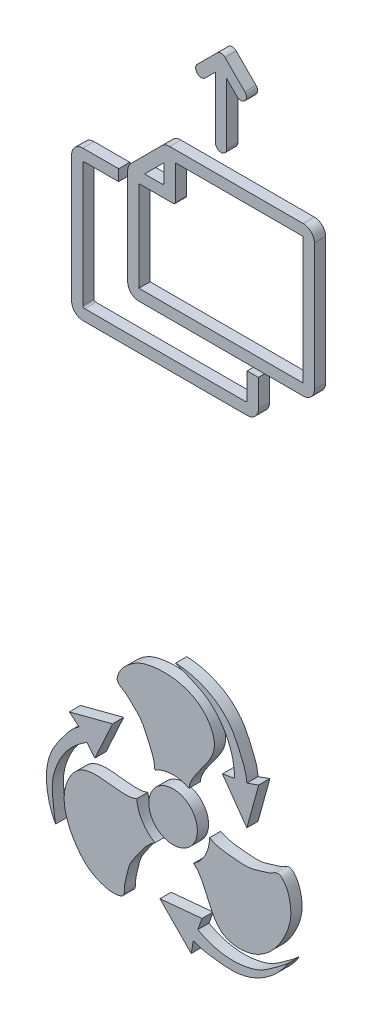
SolidWorks part; units mm, degrees
ref_plane "Plan de face" through (0, 0, 0) normal (0, 0, 1) x (1, 0, 0)
ref_plane "Plan de dessus" through (0, 0, 0) normal (0, 1, 0) x (1, 0, 0)
ref_plane "Plan de droite" through (0, 0, 0) normal (1, 0, 0) x (0, 0, -1)
sketch "Esquisse1" plane through (0, 0, 0) normal (0, 0, 1) x (1, 0, 0)
  line L0 (79.9524, -9.5695) -> (79.2967, -9.6893) construction
  line L1 (79.2967, -9.6893) -> (80.6081, -11.5354) construction
  line L2 (80.6081, -11.5354) -> (81.2446, -9.231) construction
  line L3 (81.2446, -9.231) -> (80.6081, -9.4601) construction
  line L4 (72.0398, -11.8622) -> (72.4714, -12.3701)
  line L5 (72.4714, -12.3701) -> (73.4145, -10.3114)
  line L6 (73.4145, -10.3114) -> (71.1005, -10.9123)
  line L7 (71.1005, -10.9123) -> (71.6172, -11.349)
  line L8 (72.0398, -11.8622) -> (72.4714, -12.3701)
  line L9 (72.4714, -12.3701) -> (73.4145, -10.3114)
  line L10 (73.4145, -10.3114) -> (71.1005, -10.9123)
  line L11 (71.1005, -10.9123) -> (71.6172, -11.349)
  line L12 (77.9816, -17.5683) -> (78.2057, -16.9406) construction
  line L13 (78.2057, -16.9406) -> (75.9512, -17.1532) construction
  line L14 (75.9512, -17.1532) -> (77.6286, -18.8567) construction
  line L15 (77.6286, -18.8567) -> (77.7484, -18.1908) construction
  line L16 (79.9524, -9.5695) -> (79.2967, -9.6893)
  line L17 (79.2967, -9.6893) -> (80.6081, -11.5354)
  line L18 (80.6081, -11.5354) -> (81.2446, -9.231)
  line L19 (81.2446, -9.231) -> (80.6081, -9.4601)
  line L20 (77.9816, -17.5683) -> (78.2057, -16.9406)
  line L21 (78.2057, -16.9406) -> (75.9512, -17.1532)
  line L22 (75.9512, -17.1532) -> (77.6286, -18.8567)
  line L23 (77.6286, -18.8567) -> (77.7484, -18.1908)
  line L24 (78.3769, 22.1272) -> (78.9254, 22.6757) construction
  line L25 (78.9254, 22.6757) -> (78.9254, 19.4) construction
  line L26 (79.5254, 19.4) -> (79.5254, 22.6757) construction
  line L27 (79.5254, 22.6757) -> (80.0739, 22.1272) construction
  line L28 (80.4982, 22.5515) -> (79.4375, 23.6121) construction
  line L29 (79.0133, 23.6121) -> (77.9526, 22.5515) construction
  line L30 (74.8254, 10) -> (83.6254, 10) construction
  line L31 (84.2254, 10.6) -> (84.2254, 17.4) construction
  line L32 (83.6254, 18) -> (76.4739, 18) construction
  line L33 (76.0497, 17.8243) -> (74.4011, 16.1757) construction
  line L34 (74.2254, 15.7515) -> (74.2254, 10.6) construction
  line L35 (71.8254, 7.6) -> (80.6254, 7.6) construction
  line L36 (81.2254, 8.2) -> (81.2254, 9.6641) construction
  line L37 (81.2254, 9.6641) -> (80.6254, 9.6641) construction
  line L38 (80.6254, 9.6641) -> (80.6254, 8.3) construction
  line L39 (80.5254, 8.2) -> (71.9254, 8.2) construction
  line L40 (71.8254, 8.3) -> (71.8254, 14.9) construction
  line L41 (71.9254, 15) -> (73.7394, 15) construction
  line L42 (73.7394, 15) -> (73.7394, 15.6) construction
  line L43 (73.7394, 15.6) -> (71.8254, 15.6) construction
  line L44 (71.2254, 15) -> (71.2254, 8.2) construction
  line L45 (78.3769, 22.1272) -> (78.9254, 22.6757)
  line L46 (78.9254, 22.6757) -> (78.9254, 19.4)
  line L47 (79.5254, 19.4) -> (79.5254, 22.6757)
  line L48 (79.5254, 22.6757) -> (80.0739, 22.1272)
  line L49 (80.4982, 22.5515) -> (79.4375, 23.6121)
  line L50 (79.0133, 23.6121) -> (77.9526, 22.5515)
  line L51 (74.8254, 10) -> (83.6254, 10)
  line L52 (84.2254, 10.6) -> (84.2254, 17.4)
  line L53 (83.6254, 18) -> (76.4739, 18)
  line L54 (76.0497, 17.8243) -> (74.4011, 16.1757)
  line L55 (74.2254, 15.7515) -> (74.2254, 10.6)
  line L56 (71.8254, 7.6) -> (80.6254, 7.6)
  line L57 (81.2254, 8.2) -> (81.2254, 9.6641)
  line L58 (81.2254, 9.6641) -> (80.6254, 9.6641)
  line L59 (80.6254, 9.6641) -> (80.6254, 8.3)
  line L60 (80.5254, 8.2) -> (71.9254, 8.2)
  line L61 (71.8254, 8.3) -> (71.8254, 14.9)
  line L62 (71.9254, 15) -> (73.7394, 15)
  line L63 (73.7394, 15) -> (73.7394, 15.6)
  line L64 (73.7394, 15.6) -> (71.8254, 15.6)
  line L65 (71.2254, 15) -> (71.2254, 8.2)
  line L69 (75.1254, 16.0515) -> (76.0739, 16.0515)
  line L70 (76.1739, 16.1515) -> (76.1739, 17.1)
  line L71 (76.1739, 17.1) -> (75.1254, 16.0515)
  line L72 (76.6739, 15.4515) -> (74.8254, 15.4515)
  line L73 (74.8254, 15.4515) -> (74.8254, 10.6)
  line L74 (74.8254, 10.6) -> (83.6254, 10.6)
  line L75 (83.6254, 10.6) -> (83.6254, 17.4)
  line L76 (83.6254, 17.4) -> (76.7739, 17.4)
  line L77 (76.7739, 17.4) -> (76.7739, 15.5515)
  line L78 (76.6739, 15.4515) -> (74.8254, 15.4515)
  line L79 (74.8254, 15.4515) -> (74.8254, 10.6)
  line L80 (74.8254, 10.6) -> (83.6254, 10.6)
  line L81 (83.6254, 10.6) -> (83.6254, 17.4)
  line L82 (83.6254, 17.4) -> (76.7739, 17.4)
  line L83 (76.7739, 17.4) -> (76.7739, 15.5515)
  line L84 (75.1254, 16.0515) -> (76.0739, 16.0515)
  line L85 (76.1739, 16.1515) -> (76.1739, 17.1)
  line L86 (76.1739, 17.1) -> (75.1254, 16.0515)
  arc A0 (77.7481, -14.6167) -> (78.6079, -12.9946) centre (76.6579, -13) ccw construction
  arc A1 (74.7127, -13.1358) -> (75.6876, -14.6914) centre (76.6579, -13) ccw
  arc A2 (74.7127, -13.1358) -> (75.6876, -14.6914) centre (76.6579, -13) ccw
  circle A3 centre (76.6579, -13) radius 1.3 construction
  arc A4 (77.513, -11.2475) -> (75.6783, -11.314) centre (76.6579, -13) ccw construction
  arc A5 (77.7481, -14.6167) -> (78.6079, -12.9946) centre (76.6579, -13) ccw
  circle A6 centre (76.6579, -13) radius 1.3
  arc A7 (77.513, -11.2475) -> (75.6783, -11.314) centre (76.6579, -13) ccw
  arc A8 (78.9254, 19.4) -> (79.5254, 19.4) centre (79.2254, 19.4) ccw construction
  arc A9 (80.0739, 22.1272) -> (80.4982, 22.5515) centre (80.2861, 22.3393) ccw construction
  arc A10 (79.4375, 23.6121) -> (79.0133, 23.6121) centre (79.2254, 23.4) ccw construction
  arc A11 (77.9526, 22.5515) -> (78.3769, 22.1272) centre (78.1647, 22.3393) ccw construction
  arc A12 (74.2254, 10.6) -> (74.8254, 10) centre (74.8254, 10.6) ccw construction
  arc A13 (83.6254, 10) -> (84.2254, 10.6) centre (83.6254, 10.6) ccw construction
  arc A14 (84.2254, 17.4) -> (83.6254, 18) centre (83.6254, 17.4) ccw construction
  arc A15 (76.4739, 18) -> (76.0497, 17.8243) centre (76.4739, 17.4) ccw construction
  arc A16 (74.4011, 16.1757) -> (74.2254, 15.7515) centre (74.8254, 15.7515) ccw construction
  arc A17 (71.2254, 8.2) -> (71.8254, 7.6) centre (71.8254, 8.2) ccw construction
  arc A18 (80.6254, 7.6) -> (81.2254, 8.2) centre (80.6254, 8.2) ccw construction
  arc A19 (80.5254, 8.2) -> (80.6254, 8.3) centre (80.5254, 8.3) ccw construction
  arc A20 (71.8254, 8.3) -> (71.9254, 8.2) centre (71.9254, 8.3) ccw construction
  arc A21 (71.9254, 15) -> (71.8254, 14.9) centre (71.9254, 14.9) ccw construction
  arc A22 (71.8254, 15.6) -> (71.2254, 15) centre (71.8254, 15) ccw construction
  arc A23 (78.9254, 19.4) -> (79.5254, 19.4) centre (79.2254, 19.4) ccw
  arc A24 (80.0739, 22.1272) -> (80.4982, 22.5515) centre (80.2861, 22.3393) ccw
  arc A25 (79.4375, 23.6121) -> (79.0133, 23.6121) centre (79.2254, 23.4) ccw
  arc A26 (77.9526, 22.5515) -> (78.3769, 22.1272) centre (78.1647, 22.3393) ccw
  arc A27 (74.2254, 10.6) -> (74.8254, 10) centre (74.8254, 10.6) ccw
  arc A28 (83.6254, 10) -> (84.2254, 10.6) centre (83.6254, 10.6) ccw
  arc A29 (84.2254, 17.4) -> (83.6254, 18) centre (83.6254, 17.4) ccw
  arc A30 (76.4739, 18) -> (76.0497, 17.8243) centre (76.4739, 17.4) ccw
  arc A31 (74.4011, 16.1757) -> (74.2254, 15.7515) centre (74.8254, 15.7515) ccw
  arc A32 (71.2254, 8.2) -> (71.8254, 7.6) centre (71.8254, 8.2) ccw
  arc A33 (80.6254, 7.6) -> (81.2254, 8.2) centre (80.6254, 8.2) ccw
  arc A34 (80.5254, 8.2) -> (80.6254, 8.3) centre (80.5254, 8.3) ccw
  arc A35 (71.8254, 8.3) -> (71.9254, 8.2) centre (71.9254, 8.3) ccw
  arc A36 (71.9254, 15) -> (71.8254, 14.9) centre (71.9254, 14.9) ccw
  arc A37 (71.8254, 15.6) -> (71.2254, 15) centre (71.8254, 15) ccw
  arc A39 (76.6739, 15.4515) -> (76.7739, 15.5515) centre (76.6739, 15.5515) ccw
  arc A40 (76.6739, 15.4515) -> (76.7739, 15.5515) centre (76.6739, 15.5515) ccw
  arc A41 (76.0739, 16.0515) -> (76.1739, 16.1515) centre (76.0739, 16.1515) ccw
  arc A42 (76.0739, 16.0515) -> (76.1739, 16.1515) centre (76.0739, 16.1515) ccw
  spline S0 degree 3 poles (-986.9395, -1699.3238) (62.4292, 5.9478) (67.3176, -1.6894) (78.5016, -6.5296) (79.1253, -7.1762) (89.0233, -22.4082) (-20.0418, -101.5141) (-363.9995, 1938.4037) knots -6.29078 -6.29078 -6.29078 -6.29078 0.178257 0.349466 0.520702 0.67701 10.59595 10.59595 10.59595 10.59595 only from (76.7877, -5.8062) to (79.9524, -9.5695) construction
  spline S1 degree 3 poles (-1310.8592, 2647.6474) (157.2924, -147.1266) (78.7574, -3.2975) (70.949, -14.0886) (70.7573, -15.1114) (70.9823, -16.1104) (71.4854, -16.9976) (72.1045, -17.7043) (72.7797, -18.0183) (73.3139, -18.1483) (73.6855, -18.1292) (73.973, -18.0419) (74.0642, -17.8037) (74.0332, -17.4898) (74.1701, -16.9967) (74.2853, -16.3513) (81.3172, -6.8993) (74.0587, 6.1031) (2524.0484, -1748.0053) knots -2.232401 -2.232401 -2.232401 -2.232401 0.218054 0.299963 0.364831 0.441427 0.515607 0.585452 0.640595 0.674668 0.702895 0.722682 0.733413 0.755078 0.790335 0.843337 0.895224 3.300468 3.300468 3.300468 3.300468 only from (74.7127, -13.1358) to (75.6876, -14.6914)
  spline S2 degree 3 poles (74.7127, -13.1358) (73.9427, -13.4922) (72.0458, -12.5728) (70.949, -14.0886) (70.7573, -15.1114) (70.9823, -16.1104) (71.4854, -16.9976) (72.1045, -17.7043) (72.7797, -18.0183) (73.3139, -18.1483) (73.6855, -18.1292) (73.973, -18.0419) (74.0642, -17.8037) (74.0332, -17.4898) (74.1701, -16.9967) (74.2853, -16.3513) (74.8726, -15.5618) (75.254, -14.9566) (75.6876, -14.6914) knots 0 0 0 0 0.218054 0.299963 0.364831 0.441427 0.515607 0.585452 0.640595 0.674668 0.702895 0.722682 0.733413 0.755078 0.790335 0.843337 0.895224 1 1 1 1
  spline S3 degree 3 poles (-1849.7124, -532.315) (85.3267, -29.7589) (84.523, -17.6622) (79.8518, -7.3498) (79.2096, -6.6321) (61.3662, 3.9484) (-12.4961, -117.8122) (1528.7042, -1376.5555) knots -5.309599 -5.309599 -5.309599 -5.309599 0.231711 0.386988 0.549382 0.722551 11.03605 11.03605 11.03605 11.03605 only from (80.6081, -9.4601) to (76.7877, -5.8062) construction
  spline S4 degree 3 poles (3068.3915, -118.4662) (66.0791, -36.9895) (71.725, -28.4059) (70.1326, -14.6385) (70.3807, -13.7751) (79.7399, 4.6067) (237.7625, -68.9658) (-2168.6086, -2001.3866) knots -7.225713 -7.225713 -7.225713 -7.225713 0.178257 0.349466 0.520702 0.67701 11.98457 11.98457 11.98457 11.98457 only from (70.363, -16.4846) to (72.0398, -11.8622)
  spline S5 degree 3 poles (2190.6093, -2134.6263) (89.7471, 4.7427) (77.666, -2.5976) (70.1677, -13.0591) (69.8673, -13.9741) (69.592, -37.641) (255.6841, -38.3317) (682.536, 2914.8139) knots -6.111817 -6.111817 -6.111817 -6.111817 0.231711 0.386988 0.549382 0.722551 12.537012 12.537012 12.537012 12.537012 only from (71.6172, -11.349) to (70.363, -16.4846)
  spline S6 degree 3 poles (70.363, -16.4846) (70.2961, -16.1747) (70.2396, -15.564) (70.1326, -14.6385) (70.3807, -13.7751) (70.904, -12.7473) (71.5497, -12.1504) (72.0398, -11.8622) knots 0 0 0 0 0.178257 0.349466 0.520702 0.67701 1 1 1 1
  spline S7 degree 3 poles (71.6172, -11.349) (71.2386, -11.5987) (70.7861, -12.1963) (70.1677, -13.0591) (69.8673, -13.9741) (69.8534, -15.1682) (70.1065, -16.0139) (70.363, -16.4846) knots 0 0 0 0 0.231711 0.386988 0.549382 0.722551 1 1 1 1
  spline S8 degree 3 poles (-851.9426, 1751.2643) (100.1816, -10.1514) (91.1233, -10.5663) (81.3396, -17.8319) (80.4678, -18.0487) (62.3275, -19.0047) (48.3523, 115.0015) (1986.9518, -607.0813) knots -6.29078 -6.29078 -6.29078 -6.29078 0.178257 0.349466 0.520702 0.67701 10.59595 10.59595 10.59595 10.59595 only from (82.8231, -16.7093) to (77.9816, -17.5683) construction
  spline S9 degree 3 poles (590.1031, 1914.9431) (57.8099, -12.128) (68.6878, -17.4803) (79.9542, -18.5911) (80.8968, -18.3938) (98.9816, -8.2312) (30.4649, 116.6157) (-1830.2389, -588.7312) knots -5.309599 -5.309599 -5.309599 -5.309599 0.231711 0.386988 0.549382 0.722551 11.03605 11.03605 11.03605 11.03605 only from (77.7484, -18.1908) to (82.8231, -16.7093) construction
  spline S10 degree 3 poles (-999.5227, -1699.6234) (133.9996, 93.243) (68.707, -16.1879) (80.4551, -17.3998) (81.4367, -17.0544) (82.1894, -16.3601) (82.7062, -15.4808) (83.0087, -14.5912) (82.943, -13.8495) (82.7885, -13.3218) (82.5861, -13.0096) (82.3668, -12.8043) (82.1149, -12.8444) (81.8585, -13.0281) (81.3631, -13.1562) (80.7465, -13.3791) (70.4561, -12.1797) (63.3521, -21.8661) (258.2112, 1978.8032) knots -1.9381 -1.9381 -1.9381 -1.9381 0.218054 0.299963 0.364831 0.441427 0.515607 0.585452 0.640595 0.674668 0.702895 0.722682 0.733413 0.755078 0.790335 0.843337 0.895224 2.997749 2.997749 2.997749 2.997749 only from (77.7481, -14.6167) to (78.6079, -12.9946) construction
  spline S11 degree 3 poles (2075.4069, -101.6881) (-44.0221, -16.4622) (83.3942, -18.2918) (78.5696, -7.5116) (77.7797, -6.8343) (76.8021, -6.5296) (75.7822, -6.5216) (74.8606, -6.7044) (74.251, -7.1322) (73.8713, -7.5299) (73.7021, -7.8612) (73.634, -8.1538) (73.7947, -8.3519) (74.082, -8.4821) (74.4406, -8.8471) (74.942, -9.2696) (79.0484, -18.781) (90.9891, -20.0901) (-1739.0709, -851.6719) knots -1.9381 -1.9381 -1.9381 -1.9381 0.218054 0.299963 0.364831 0.441427 0.515607 0.585452 0.640595 0.674668 0.702895 0.722682 0.733413 0.755078 0.790335 0.843337 0.895224 2.997749 2.997749 2.997749 2.997749 only from (77.513, -11.2475) to (75.6783, -11.314) construction
  spline S12 degree 3 poles (76.7877, -5.8062) (77.0895, -5.9032) (77.6466, -6.1596) (78.5016, -6.5296) (79.1253, -7.1762) (79.7537, -8.1433) (79.9478, -9.0009) (79.9524, -9.5695) knots 0 0 0 0 0.178257 0.349466 0.520702 0.67701 1 1 1 1
  spline S13 degree 3 poles (80.6081, -9.4601) (80.5811, -9.0074) (80.2898, -8.3167) (79.8518, -7.3498) (79.2096, -6.6321) (78.1825, -6.023) (77.3235, -5.8194) (76.7877, -5.8062) knots 0 0 0 0 0.231711 0.386988 0.549382 0.722551 1 1 1 1
  spline S14 degree 3 poles (82.8231, -16.7093) (82.5881, -16.9222) (82.0875, -17.2764) (81.3396, -17.8319) (80.4678, -18.0487) (79.3161, -18.1094) (78.4763, -17.8487) (77.9816, -17.5683) knots 0 0 0 0 0.178257 0.349466 0.520702 0.67701 1 1 1 1
  spline S15 degree 3 poles (77.7484, -18.1908) (78.154, -18.3939) (78.8978, -18.487) (79.9542, -18.5911) (80.8968, -18.3938) (81.9379, -17.8088) (82.5438, -17.1667) (82.8231, -16.7093) knots 0 0 0 0 0.231711 0.386988 0.549382 0.722551 1 1 1 1
  spline S16 degree 3 poles (77.7481, -14.6167) (78.4417, -15.1053) (78.594, -17.2078) (80.4551, -17.3998) (81.4367, -17.0544) (82.1894, -16.3601) (82.7062, -15.4808) (83.0087, -14.5912) (82.943, -13.8495) (82.7885, -13.3218) (82.5861, -13.0096) (82.3668, -12.8043) (82.1149, -12.8444) (81.8585, -13.0281) (81.3631, -13.1562) (80.7465, -13.3791) (79.7691, -13.2652) (79.0543, -13.2375) (78.6079, -12.9946) knots 0 0 0 0 0.218054 0.299963 0.364831 0.441427 0.515607 0.585452 0.640595 0.674668 0.702895 0.722682 0.733413 0.755078 0.790335 0.843337 0.895224 1 1 1 1
  spline S17 degree 3 poles (77.513, -11.2475) (77.5893, -10.4025) (79.3339, -9.2194) (78.5696, -7.5116) (77.7797, -6.8343) (76.8021, -6.5296) (75.7822, -6.5216) (74.8606, -6.7044) (74.251, -7.1322) (73.8713, -7.5299) (73.7021, -7.8612) (73.634, -8.1538) (73.7947, -8.3519) (74.082, -8.4821) (74.4406, -8.8471) (74.942, -9.2696) (75.332, -10.173) (75.6654, -10.8059) (75.6783, -11.314) knots 0 0 0 0 0.218054 0.299963 0.364831 0.441427 0.515607 0.585452 0.640595 0.674668 0.702895 0.722682 0.733413 0.755078 0.790335 0.843337 0.895224 1 1 1 1
  dimension "D1" = 0
  dimension "D2" = 0
  dimension "D3" = 0
  dimension "D4" = 0
extrude "Boss.-Extru.1" add sketch "Esquisse1" along normal blind 0.6
